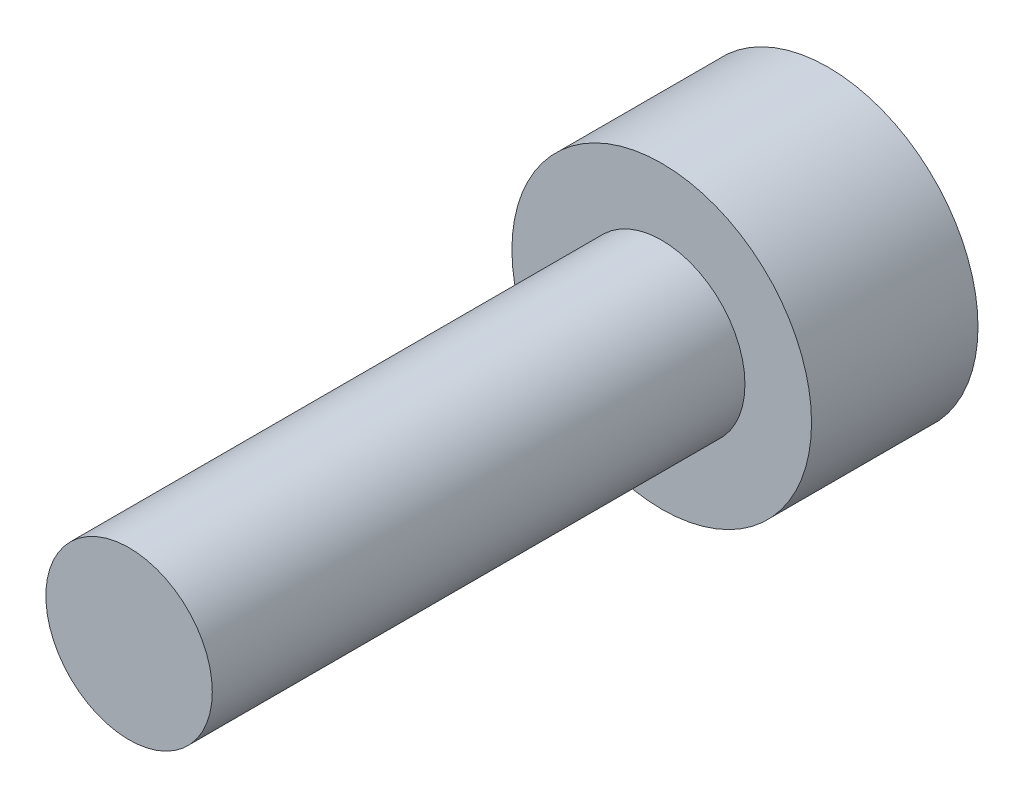
SolidWorks part; units mm, degrees
material "AISI 304"
ref_plane "前视基准面" through (0, 0, 0) normal (0, 0, 1) x (1, 0, 0)
ref_plane "上视基准面" through (0, 0, 0) normal (0, 1, 0) x (1, 0, 0)
ref_plane "右视基准面" through (0, 0, 0) normal (1, 0, 0) x (0, 0, -1)
sketch "草图1" plane through (0, 0, 0) normal (0, 0, 1) x (1, 0, 0)
  circle A0 centre (0, 0) radius 2.25
  dimension "D1" = 4.5
extrude "凸台-拉伸1" add sketch "草图1" along normal blind 2.5
sketch "草图2" plane through (0, 0, 2.5) normal (0, 0, 1) x (1, 0, 0)
  circle A0 centre (0, 0) radius 1.25
  dimension "D1" = 2.5
extrude "凸台-拉伸2" add sketch "草图2" along normal blind 8
cosmetic thread "装饰螺纹线1" parameters "D2"=2.013
sketch "草图3" plane through (0, 0, 0) normal (0, 0, -1) x (-1, 0, 0)
  line L1 (1.1547, 0) -> (0.5774, 1)
  line L2 (0.5774, 1) -> (-0.5774, 1)
  line L3 (-0.5774, 1) -> (-1.1547, 0)
  line L4 (-1.1547, 0) -> (-0.5774, -1)
  line L5 (-0.5774, -1) -> (0.5774, -1)
  line L6 (0.5774, -1) -> (1.1547, 0)
  circle A0 centre (0, 0) radius 1 construction
  dimension "D1" = 2
extrude "切除-拉伸1" cut sketch "草图3" against normal blind 1
